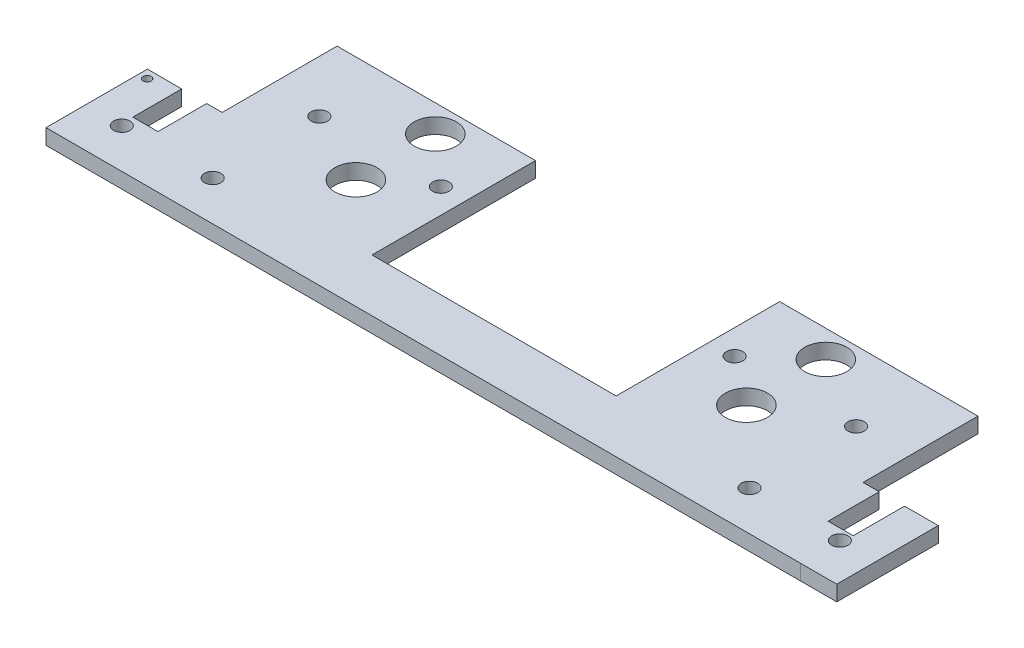
SolidWorks part; units mm, degrees
material "Copper"
ref_plane "Front Plane" through (0, 0, 0) normal (0, 0, 1) x (1, 0, 0)
ref_plane "Top Plane" through (0, 0, 0) normal (0, 1, 0) x (1, 0, 0)
ref_plane "Right Plane" through (0, 0, 0) normal (1, 0, 0) x (0, 0, -1)
sketch "Sketch1" plane through (0, 0, 0) normal (0, 1, 0) x (1, 0, 0)
  line L0 (44.3513, -40.0144) -> (37.1363, -40.0144)
  line L1 (0, 0) -> (0, -46.6159) construction
  line L2 (-19.6486, -28.7674) -> (44.3513, -28.7674) construction
  line L3 (-36.4337, -40.0144) -> (-36.4337, -46.6159)
  line L4 (37.1363, -40.0144) -> (37.1363, -46.6159)
  line L5 (-36.4337, -40.0144) -> (-43.6487, -40.0144)
  line L6 (-32.4727, -10.3704) -> (-32.4727, -29.6479)
  line L7 (-32.4727, 38.1938) -> (-32.4727, -29.6479) construction
  line L8 (-19.6486, -20.6394) -> (46.7444, -20.6394) construction
  line L9 (-42.3787, -29.6159) -> (-32.4727, -29.6479)
  line L10 (-12.1556, -10.3704) -> (-32.4727, -10.3704)
  line L11 (29.9683, -46.6159) -> (37.1363, -46.6159)
  line L12 (44.3513, -40.0144) -> (44.3513, -31.6519)
  line L13 (42.3513, -29.6159) -> (38.7463, -29.6159)
  line L14 (38.7463, -29.6159) -> (33.1753, -29.6479)
  line L15 (-11.5577, -34.6159) -> (-12.1556, -34.6159)
  line L16 (-12.1556, -34.6159) -> (-12.1556, -10.3704)
  line L17 (33.1753, -29.6479) -> (33.1753, 37.3661) construction
  line L18 (33.1753, -12.9294) -> (33.1753, -29.6479)
  line L19 (12.8581, -10.3704) -> (33.1753, -10.3704)
  line L20 (33.1753, -10.3704) -> (33.1753, -12.9294)
  line L21 (-43.6487, -29.6479) -> (-43.6487, -44.6339) construction
  line L22 (-43.6487, -30.8859) -> (-43.6487, -40.0144)
  line L23 (-36.4337, -46.6159) -> (-30.0837, -46.6159)
  line L24 (-30.0837, -46.6159) -> (29.9683, -46.6159)
  line L25 (-11.5577, -34.6159) -> (12.2603, -34.6159)
  line L28 (-43.6487, -30.8859) -> (-43.6487, -29.6479)
  line L29 (-43.6487, -29.6479) -> (-42.3787, -29.6159)
  line L30 (44.3513, -31.6519) -> (44.3513, -29.6159)
  line L31 (44.3513, -29.6159) -> (42.3513, -29.6159)
  line L32 (12.2603, -34.6159) -> (12.8581, -34.6159)
  line L33 (12.8581, -34.6159) -> (12.8581, -10.3704)
  circle A0 centre (-36.4337, -35.9659) radius 0.8382
  circle A1 centre (37.1363, -35.9839) radius 0.8382
  circle A2 centre (-19.6486, -28.7674) radius 2.159
  circle A3 centre (-19.6486, -20.6394) radius 2.159
  circle A4 centre (20.3514, -20.6394) radius 2.159
  circle A5 centre (20.3514, -28.7674) radius 2.159
  dimension "D2" = 1.6764
  dimension "D5" = 1.6764
  dimension "D8" = 4.318
  dimension "D3" = 4.318
  dimension "D6" = 4.318
  dimension "D9" = 4.318
  dimension "D10" = 8.128
  dimension "D1" = 12
  dimension "D4" = 0
  dimension "D7" = 0
  dimension "D11" = 8.128
  dimension "D12" = 0
extrude "Boss-Extrude1" add sketch "Sketch1" along normal blind 1.575
sketch "Sketch2" plane through (0, 0, 0) normal (0, -1, 0) x (1, 0, 0)
  line L2 (-49.1064, 40.0139) -> (37.1363, 40.0139)
  line L4 (-49.1064, 40.0139) -> (-49.1064, 46.6159)
  line L6 (-49.1064, 46.6159) -> (37.1363, 46.6159)
  line L7 (37.1363, 40.0139) -> (37.1363, 46.6159)
  line L10 (-49.1064, 40.0139) -> (37.1363, 46.6159) construction
  line L12 (-49.1064, 46.6159) -> (37.1363, 40.0139) construction
  point P0 (-5.985, 43.3149)
  dimension "D1" = 6.602
extrude "Cut-Extrude1" cut sketch "Sketch2" against normal through all
sketch "Sketch3" plane through (0, 0, 0) normal (0, -1, 0) x (1, 0, 0)
  line L0 (-40.1487, 40.0139) -> (-40.1487, 29.6232)
  line L1 (-43.6487, 40.0139) -> (37.1363, 40.0139) construction
  line L3 (-32.4727, 29.6479) -> (-42.3787, 29.6159) construction
  line L4 (-40.1487, 29.6232) -> (-34.7737, 29.6405)
  line L8 (-40.1487, 40.0139) -> (-46.7728, 40.0139)
  line L9 (-46.7728, 40.0139) -> (-46.7728, 8.9756)
  line L10 (-46.7728, 8.9756) -> (-34.7737, 8.9756)
  line L11 (-34.7737, 29.6405) -> (-34.7737, 8.9756)
  dimension "D1" = 6.6241
  dimension "D2" = 5.375
  dimension "D3" = 31.0383
  dimension "D4" = 20.6649
  dimension "D5" = 10.3908
extrude "Cut-Extrude2" cut sketch "Sketch3" against normal through all
sketch "Sketch4" plane through (0, 0, 0) normal (0, -1, 0) x (1, 0, 0)
  line L0 (40.8513, 40.0144) -> (40.8513, 32.4201)
  line L1 (35.4763, 29.6159) -> (35.4763, 10.3704)
  line L2 (35.4763, 10.3704) -> (54.7109, 10.3704)
  line L7 (54.7109, 10.3704) -> (54.7109, 40.0144)
  line L8 (37.1363, 40.0144) -> (44.3513, 40.0144) construction
  line L11 (44.3513, 40.0144) -> (44.3513, 29.6159) construction
  line L12 (40.8513, 32.4201) -> (40.8513, 29.6159)
  line L13 (44.3513, 29.6159) -> (38.7463, 29.6159) construction
  line L14 (40.8513, 29.6159) -> (35.4763, 29.6159)
  line L15 (40.8513, 40.0144) -> (54.7109, 40.0144)
  dimension "D2" = 3.5
extrude "Cut-Extrude3" cut sketch "Sketch4" against normal through all
sketch "Sketch6" plane through (0, 0, 0) normal (0, -1, 0) x (-1, 0, 0)
  circle A0 centre (27.1416, -35.9479) radius 0.8382
  circle A1 centre (27.1416, -25.0259) radius 0.8382
  circle A2 centre (14.6956, -25.0259) radius 0.8382
  circle A3 centre (-15.3981, -25.0259) radius 0.8382
  circle A4 centre (-27.8444, -25.0259) radius 0.8382
  circle A5 centre (-27.8444, -35.9479) radius 0.8382
extrude "Cut-Extrude4" cut sketch "Sketch6" against normal blind 2.54
sketch "Sketch7" plane through (0, 0, 0) normal (0, -1, 0) x (1, 0, 0)
  line L0 (-32.4727, 10.3704) -> (-32.4727, 29.6479) construction
  line L1 (-32.4727, 17.8704) -> (33.1753, 17.8704)
  line L2 (-32.4727, 17.8704) -> (-32.4727, 10.3704)
  line L3 (-32.4727, 10.3704) -> (33.1753, 10.3704)
  line L4 (33.1753, 17.8704) -> (33.1753, 10.3704)
  dimension "D1" = 7.5
extrude "Cut-Extrude5" cut sketch "Sketch7" against normal through all
sketch "Sketch11" plane through (0, 1.575, 0) normal (0, 1, 0) x (1, 0, 0)
  circle A0 centre (-39.3048, -30.495) radius 0.4126
extrude "ID HOLE" cut sketch "Sketch11" against normal through all
sketch "Sketch12" plane through (0, 0, 0) normal (0, -1, 0) x (-1, 0, 0)
  line L0 (42.3787, -29.6159) -> (32.4727, -29.6479) construction
  line L1 (36.6327, -29.6345) -> (34.0577, -29.6345)
  line L2 (36.6327, -29.6345) -> (36.6327, -34.6345)
  line L3 (36.6327, -34.6345) -> (34.0577, -34.6345)
  line L4 (34.0577, -29.6345) -> (34.0577, -34.6345)
  dimension "D1" = 2.575
  dimension "D2" = 5
  dimension "D3" = 3.516
extrude "Cut-Extrude6" cut sketch "Sketch12" against normal through all
sketch "Sketch14" plane through (0, 0, 0) normal (0, -1, 0) x (-1, 0, 0)
  line L1 (-40.8513, -40.0144) -> (-40.8513, -27.0505) construction
  line L2 (-33.1753, -17.8704) -> (-12.8581, -17.8704) construction
  line L4 (-34.8223, -34.873) -> (-37.3973, -34.873)
  line L5 (-34.8223, -34.873) -> (-34.8223, -17.8704)
  line L6 (-34.8223, -17.8704) -> (-37.3973, -17.8704)
  line L7 (-37.3973, -34.873) -> (-37.3973, -17.8704)
  dimension "D1" = 77.546
  dimension "D2" = 2.575
extrude "Cut-Extrude7" cut sketch "Sketch14" against normal through all contours L5 L6 L7 L4
